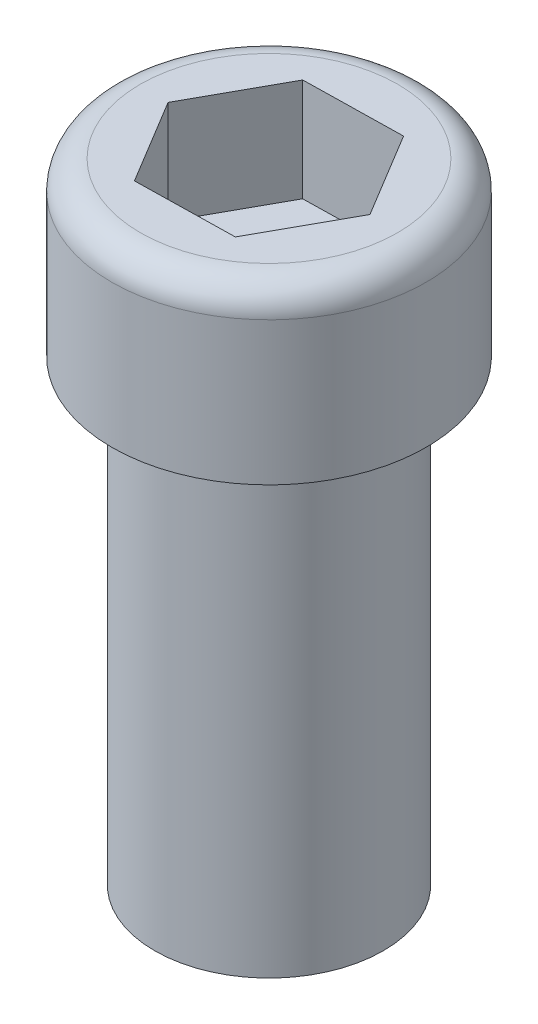
SolidWorks part; units mm, degrees
material "AISI 1020"
ref_plane "Front Plane" through (0, 0, 0) normal (0, 0, 1) x (1, 0, 0)
ref_plane "Top Plane" through (0, 0, 0) normal (0, 1, 0) x (1, 0, 0)
ref_plane "Right Plane" through (0, 0, 0) normal (1, 0, 0) x (0, 0, -1)
sketch "Sketch1" plane through (0, 0, 0) normal (0, 1, 0) x (1, 0, 0)
  circle A0 centre (0, 0) radius 2
extrude "Boss-Extrude1" add sketch "Sketch1" along normal blind 8
sketch "Sketch2" plane through (0, 8, 0) normal (0, 1, 0) x (1, 0, 0)
  circle A0 centre (0, 0) radius 2.75
extrude "Boss-Extrude2" add sketch "Sketch2" along normal blind 3
sketch "Sketch3" plane through (0, 11, 0) normal (0, 1, 0) x (1, 0, 0)
  line L1 (0.8373, 1.5162) -> (-0.8945, 1.4832)
  line L2 (-0.8945, 1.4832) -> (-1.7317, -0.033)
  line L3 (-1.7317, -0.033) -> (-0.8373, -1.5162)
  line L4 (-0.8373, -1.5162) -> (0.8945, -1.4832)
  line L5 (0.8945, -1.4832) -> (1.7317, 0.033)
  line L6 (1.7317, 0.033) -> (0.8373, 1.5162)
  circle A0 centre (0, 0) radius 1.5 construction
extrude "Cut-Extrude1" cut sketch "Sketch3" against normal blind 1.8
fillet "Fillet1" radius 0.5 1 edges at (0, 11, 2.75)
